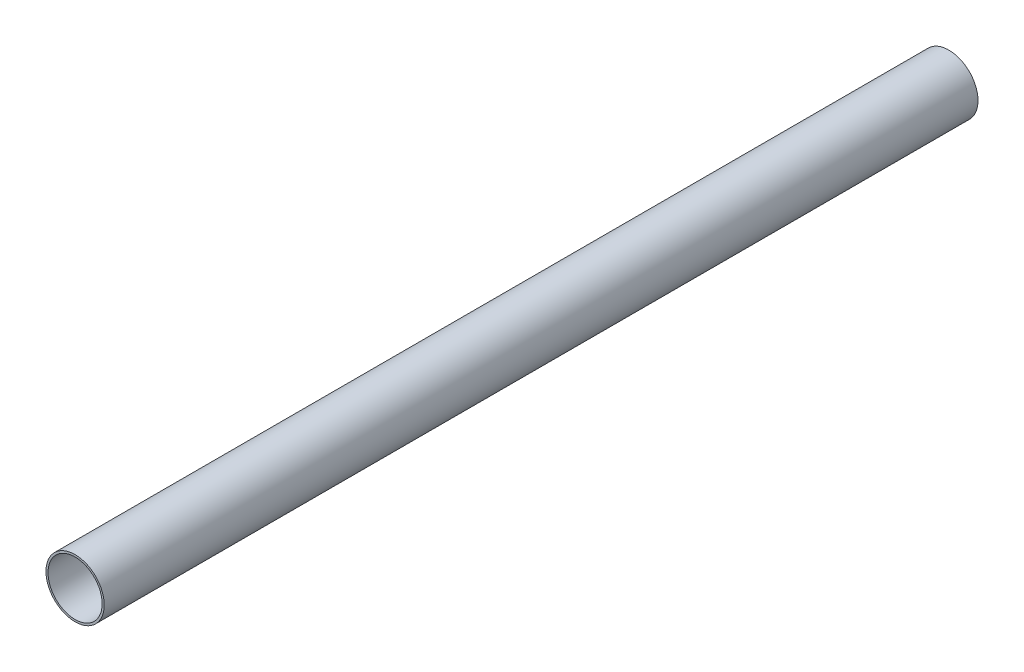
SolidWorks part; units mm, degrees
ref_plane "Front Plane" through (0, 0, 0) normal (0, 0, 1) x (1, 0, 0)
ref_plane "Top Plane" through (0, 0, 0) normal (0, 1, 0) x (1, 0, 0)
ref_plane "Right Plane" through (0, 0, 0) normal (1, 0, 0) x (0, 0, -1)
sketch "Sketch2" plane through (0, 0, 0) normal (0, 0, 1) x (1, 0, 0)
  circle A0 centre (0, 0) radius 12.7
  circle A1 centre (0, 0) radius 11.811
  dimension "D1" = 25.4
  dimension "D2" = 0.889
extrude "Boss-Extrude1" add sketch "Sketch2" along normal blind 381
sketch "Sketch3" plane through (0, 0, 0) normal (1, 0, 0) x (0, 0, -1)
  line L0 (-381, 12.7) -> (-381, -12.7) construction
  circle A0 centre (0, 0) radius 12.7
  circle A1 centre (-381, 0) radius 12.7
  dimension "D1" = 25.4
  dimension "D2" = 25.4
extrude "Cut-Extrude1" [suppressed] cut sketch "Sketch3" against normal mid plane 381
